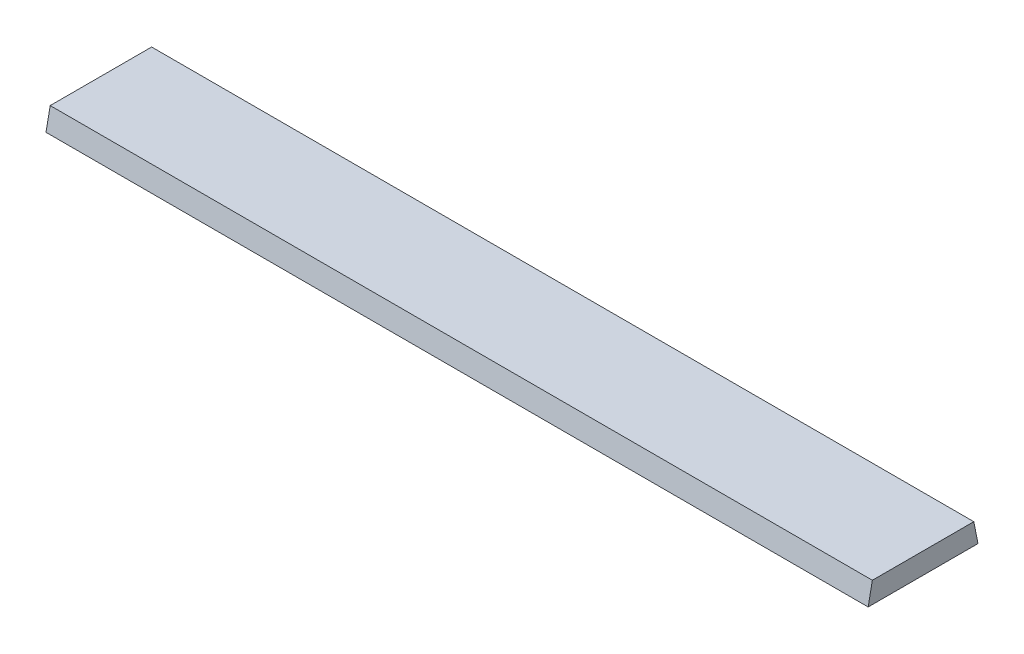
SolidWorks part; units mm, degrees
ref_plane "Front Plane" through (0, 0, 0) normal (0, 0, 1) x (1, 0, 0)
ref_plane "Top Plane" through (0, 0, 0) normal (0, 1, 0) x (1, 0, 0)
ref_plane "Right Plane" through (0, 0, 0) normal (1, 0, 0) x (0, 0, -1)
sketch "Sketch1" plane through (0, 0, 0) normal (1, 0, 0) x (0, 0, -1)
  line L0 (0, 249.4855) -> (0, 0) construction
  line L1 (49.6258, 0) -> (-49.6258, 0)
  line L2 (-49.6258, 0) -> (-45.8365, 19.05)
  line L3 (-45.8365, 19.05) -> (45.8365, 19.05)
  line L4 (49.6258, 0) -> (45.8365, 19.05)
  circle A0 centre (0, 249.4855) radius 234.95 construction
  point P7 (0, 19.05)
  dimension "Theta" = 78.75
  dimension "t" = 19.05
  dimension "R" = 234.95
  dimension "ISW" = 91.6729
extrude "Cut To Length" add sketch "Sketch1" along normal blind 742.95
sketch "Sketch2" plane through (0, 0, 0) normal (0, 0, 1) x (1, 0, 0)
  line L0 (742.95, 19.05) -> (742.95, 249.4855) construction
  line L1 (0, 249.4855) -> (742.95, 249.4855) construction
  line L2 (0, 14.5355) -> (0, 484.4355) construction
